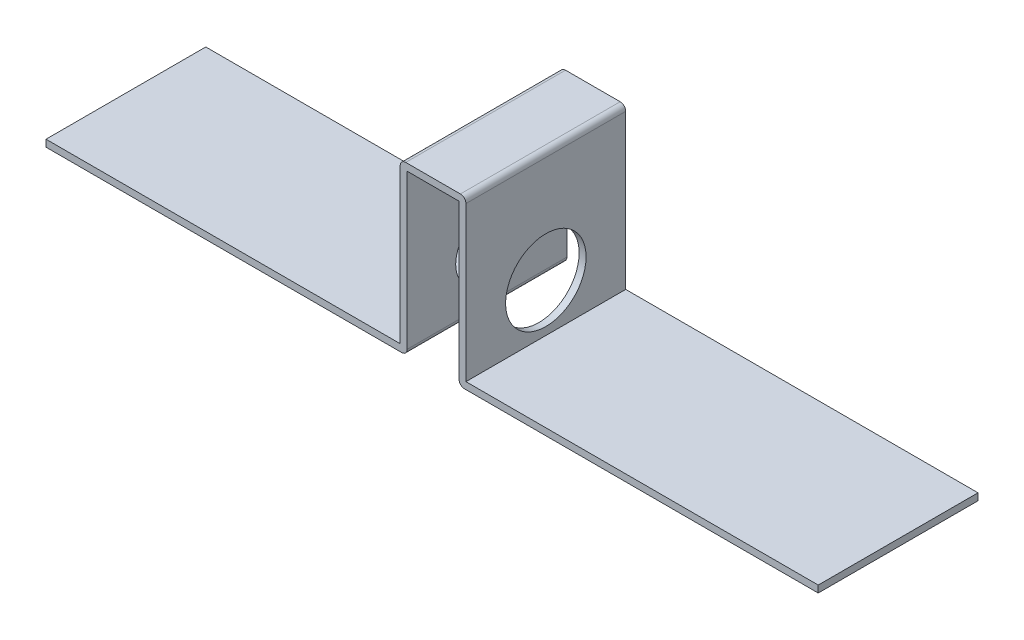
SolidWorks part; units mm, degrees
ref_plane "Front Plane" through (0, 0, 0) normal (0, 0, 1) x (1, 0, 0)
ref_plane "Top Plane" through (0, 0, 0) normal (0, 1, 0) x (1, 0, 0)
ref_plane "Right Plane" through (0, 0, 0) normal (1, 0, 0) x (0, 0, -1)
sketch "Sketch1" plane through (0, 0, 0) normal (0, 0, 1) x (1, 0, 0)
  line L0 (0, 0) -> (165.354, 0)
  line L1 (165.354, 0) -> (165.354, 73.152)
  line L2 (165.354, 73.152) -> (189.103, 73.152)
  line L3 (189.103, 73.152) -> (189.103, 0)
  line L4 (189.103, 0) -> (353.568, 0)
  line L5 (0, 3.175) -> (162.179, 3.175)
  line L6 (162.179, 3.175) -> (162.179, 76.327)
  line L7 (162.179, 76.327) -> (192.278, 76.327)
  line L8 (192.278, 76.327) -> (192.278, 3.175)
  line L9 (192.278, 3.175) -> (353.568, 3.175)
  line L10 (353.568, 3.175) -> (353.568, 0)
  line L11 (0, 3.175) -> (0, 0)
  dimension "D1" = 165.354
  dimension "D2" = 73.152
  dimension "D3" = 164.465
  dimension "D4" = 73.152
  dimension "D5" = 23.749
  dimension "D6" = 3.175
extrude "Boss-Extrude1" add sketch "Sketch1" along normal blind 73.152
sketch "Sketch2" plane through (162.179, 0, 0) normal (-1, 0, 0) x (0, 0, 1)
  line L0 (73.152, 3.175) -> (0, 3.175) construction
  line L1 (73.152, 76.327) -> (73.152, 3.175) construction
  circle A0 centre (36.576, 25.146) radius 14.351
  dimension "D1" = 21.971
  dimension "D2" = 36.576
extrude "Cut-Extrude1" cut sketch "Sketch2" against normal blind 12.7
sketch "Sketch3" plane through (192.278, 0, 0) normal (1, 0, 0) x (0, 0, -1)
  line L0 (-73.152, 3.175) -> (-73.152, 76.327) construction
  line L1 (-73.152, 3.175) -> (0, 3.175) construction
  circle A0 centre (-36.576, 25.146) radius 18.415
  point P4 (-36.576, 3.175)
  dimension "D1" = 36.576
  dimension "D2" = 21.971
extrude "Cut-Extrude2" cut sketch "Sketch3" against normal blind 12.7
fillet "Fillet1" radius 2.54 4 edges at (189.103, 0, 36.576) (165.354, 0, 36.576) (192.278, 76.327, 36.576) (162.179, 76.327, 36.576)
